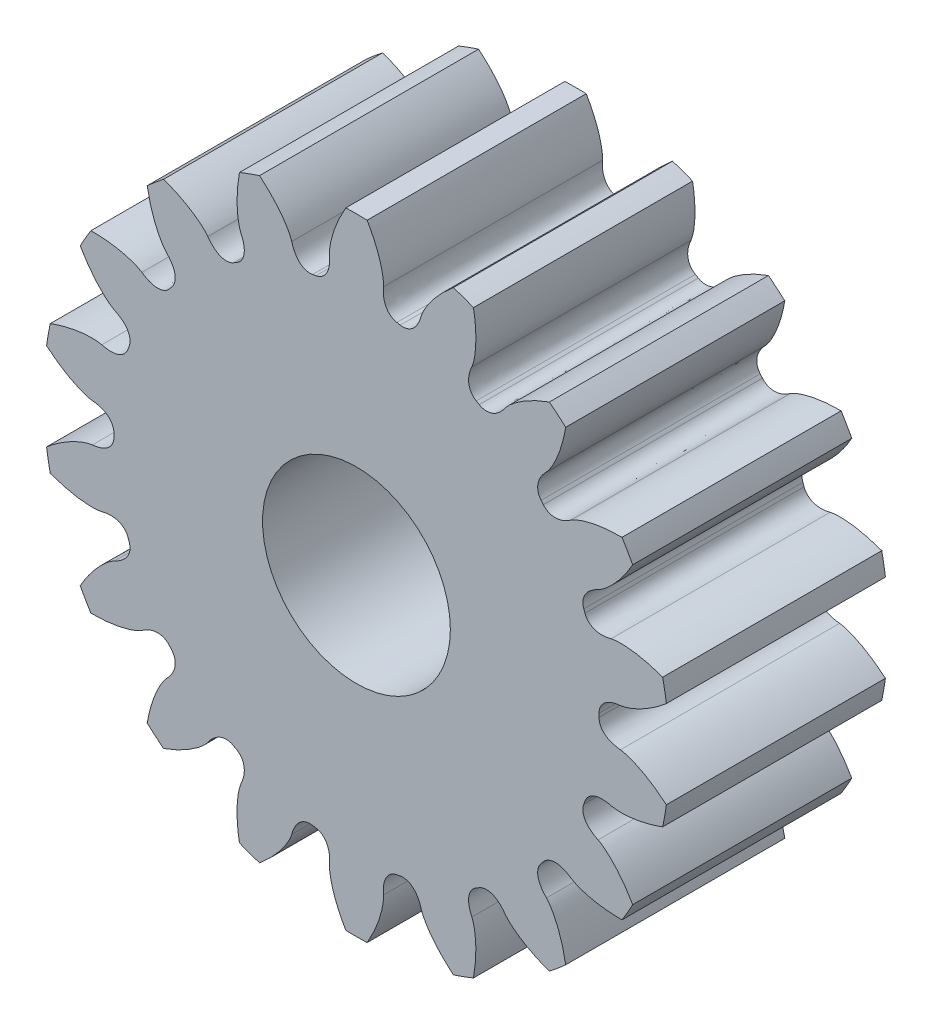
SolidWorks part; units mm, degrees
ref_plane "Спереди" through (0, 0, 0) normal (0, 0, 1) x (1, 0, 0)
ref_plane "Сверху" through (0, 0, 0) normal (0, 1, 0) x (1, 0, 0)
ref_plane "Справа" through (0, 0, 0) normal (1, 0, 0) x (0, 0, -1)
sketch "Model" plane through (0, 0, 0) normal (0, 0, 1) x (1, 0, 0)
  line L0 (-7.7, 0) -> (7.7, 0) construction
  line L1 (0, -7.7) -> (0, 7.7) construction
  arc A0 (0.1704, 4.9971) -> (-0.1704, 4.9971) centre (0, 0) ccw
  arc A1 (-0.6456, 3.8208) -> (-0.7002, 3.8112) centre (0, 0) ccw
  arc A2 (-1.549, 4.754) -> (-1.8692, 4.6375) centre (0, 0) ccw
  arc A3 (-1.9135, 3.3696) -> (-1.9614, 3.3419) centre (0, 0) ccw
  arc A4 (-3.0816, 3.9375) -> (-3.3426, 3.7185) centre (0, 0) ccw
  arc A5 (-2.9505, 2.512) -> (-2.9862, 2.4695) centre (0, 0) ccw
  arc A6 (-4.2424, 2.6461) -> (-4.4128, 2.351) centre (0, 0) ccw
  arc A7 (-3.6317, 1.3513) -> (-3.6507, 1.2993) centre (0, 0) ccw
  arc A8 (-4.8916, 1.0355) -> (-4.9508, 0.6999) centre (0, 0) ccw
  arc A9 (-3.8749, 0.0277) -> (-3.8749, -0.0277) centre (0, 0) ccw
  arc A10 (-4.9508, -0.6999) -> (-4.8916, -1.0355) centre (0, 0) ccw
  arc A11 (-3.6507, -1.2993) -> (-3.6317, -1.3513) centre (0, 0) ccw
  arc A12 (-4.4128, -2.351) -> (-4.2424, -2.6461) centre (0, 0) ccw
  arc A13 (-2.9862, -2.4695) -> (-2.9505, -2.512) centre (0, 0) ccw
  arc A14 (-3.3426, -3.7185) -> (-3.0816, -3.9375) centre (0, 0) ccw
  arc A15 (-1.9614, -3.3419) -> (-1.9135, -3.3696) centre (0, 0) ccw
  arc A16 (-1.8692, -4.6375) -> (-1.549, -4.754) centre (0, 0) ccw
  arc A17 (-0.7002, -3.8112) -> (-0.6456, -3.8208) centre (0, 0) ccw
  arc A18 (-0.1704, -4.9971) -> (0.1704, -4.9971) centre (0, 0) ccw
  arc A19 (0.6456, -3.8208) -> (0.7002, -3.8112) centre (0, 0) ccw
  arc A20 (1.549, -4.754) -> (1.8692, -4.6375) centre (0, 0) ccw
  arc A21 (1.9135, -3.3696) -> (1.9614, -3.3419) centre (0, 0) ccw
  arc A22 (3.0816, -3.9375) -> (3.3426, -3.7185) centre (0, 0) ccw
  arc A23 (2.9505, -2.512) -> (2.9862, -2.4695) centre (0, 0) ccw
  arc A24 (4.2424, -2.6461) -> (4.4128, -2.351) centre (0, 0) ccw
  arc A25 (3.6317, -1.3513) -> (3.6507, -1.2993) centre (0, 0) ccw
  arc A26 (4.8916, -1.0355) -> (4.9508, -0.6999) centre (0, 0) ccw
  arc A27 (3.8749, -0.0277) -> (3.8749, 0.0277) centre (0, 0) ccw
  arc A28 (4.9508, 0.6999) -> (4.8916, 1.0355) centre (0, 0) ccw
  arc A29 (3.6507, 1.2993) -> (3.6317, 1.3513) centre (0, 0) ccw
  arc A30 (4.4128, 2.351) -> (4.2424, 2.6461) centre (0, 0) ccw
  arc A31 (2.9862, 2.4695) -> (2.9505, 2.512) centre (0, 0) ccw
  arc A32 (3.3426, 3.7185) -> (3.0816, 3.9375) centre (0, 0) ccw
  arc A33 (1.9614, 3.3419) -> (1.9135, 3.3696) centre (0, 0) ccw
  arc A34 (1.8692, 4.6375) -> (1.549, 4.754) centre (0, 0) ccw
  arc A35 (0.7002, 3.8112) -> (0.6456, 3.8208) centre (0, 0) ccw
  circle A36 centre (0, 0) radius 4.5 construction
  spline S0 degree 3 poles (0.4314, 4.2073) (0.4264, 4.1628) (0.4271, 4.1189) (0.4335, 4.0758) (0.4372, 4.0511) (0.4421, 4.026) (0.4501, 4.0023) (0.4558, 3.9851) (0.4628, 3.968) (0.4713, 3.952) (0.4783, 3.9388) (0.4864, 3.9259) (0.4954, 3.914) (0.5034, 3.9034) (0.5123, 3.8933) (0.5218, 3.8841) (0.5307, 3.8755) (0.5403, 3.8675) (0.5504, 3.8604) (0.56, 3.8536) (0.5702, 3.8474) (0.5807, 3.8421) (0.5909, 3.837) (0.6017, 3.8326) (0.6125, 3.829) (0.6233, 3.8255) (0.6343, 3.8228) (0.6456, 3.8208) knots 0 0 0 0 1 1 1 2 2 2 3 3 3 4 4 4 5 5 5 6 6 6 7 7 7 8 8 8 9 9 9 9
  spline S1 degree 3 poles (-0.4314, 4.2073) (-0.4264, 4.1628) (-0.4271, 4.1189) (-0.4335, 4.0758) (-0.4372, 4.0511) (-0.4421, 4.026) (-0.4501, 4.0023) (-0.4558, 3.9851) (-0.4628, 3.968) (-0.4713, 3.952) (-0.4783, 3.9388) (-0.4864, 3.9259) (-0.4954, 3.914) (-0.5034, 3.9034) (-0.5123, 3.8933) (-0.5218, 3.8841) (-0.5307, 3.8755) (-0.5403, 3.8675) (-0.5504, 3.8604) (-0.56, 3.8536) (-0.5702, 3.8474) (-0.5807, 3.8421) (-0.5909, 3.837) (-0.6017, 3.8326) (-0.6125, 3.829) (-0.6233, 3.8255) (-0.6343, 3.8228) (-0.6456, 3.8208) knots 0 0 0 0 1 1 1 2 2 2 3 3 3 4 4 4 5 5 5 6 6 6 7 7 7 8 8 8 9 9 9 9
  spline S2 degree 3 poles (0.4314, 4.2073) (0.432, 4.2362) (0.431, 4.265) (0.4284, 4.2936) (0.4258, 4.3229) (0.4209, 4.352) (0.4156, 4.3809) (0.4101, 4.4104) (0.4034, 4.4397) (0.3959, 4.4687) (0.3884, 4.4983) (0.3797, 4.5277) (0.3705, 4.5568) (0.361, 4.5865) (0.3507, 4.6159) (0.3398, 4.6451) (0.3287, 4.6748) (0.3167, 4.7042) (0.3042, 4.7333) (0.2915, 4.763) (0.278, 4.7924) (0.264, 4.8215) (0.2497, 4.8511) (0.2348, 4.8805) (0.2193, 4.9095) (0.2036, 4.939) (0.1873, 4.9682) (0.1704, 4.9971) knots 0 0 0 0 1 1 1 2 2 2 3 3 3 4 4 4 5 5 5 6 6 6 7 7 7 8 8 8 9 9 9 9
  spline S3 degree 3 poles (-0.4314, 4.2073) (-0.432, 4.2362) (-0.431, 4.265) (-0.4284, 4.2936) (-0.4258, 4.3229) (-0.4209, 4.352) (-0.4156, 4.3809) (-0.4101, 4.4104) (-0.4034, 4.4397) (-0.3959, 4.4687) (-0.3884, 4.4983) (-0.3797, 4.5277) (-0.3705, 4.5568) (-0.361, 4.5865) (-0.3507, 4.6159) (-0.3398, 4.6451) (-0.3287, 4.6748) (-0.3167, 4.7042) (-0.3042, 4.7333) (-0.2915, 4.763) (-0.278, 4.7924) (-0.264, 4.8215) (-0.2497, 4.8511) (-0.2348, 4.8805) (-0.2193, 4.9095) (-0.2036, 4.939) (-0.1873, 4.9682) (-0.1704, 4.9971) knots 0 0 0 0 1 1 1 2 2 2 3 3 3 4 4 4 5 5 5 6 6 6 7 7 7 8 8 8 9 9 9 9
  spline S4 degree 3 poles (-1.0336, 4.1011) (-1.0231, 4.0576) (-1.0074, 4.0166) (-0.9866, 3.9783) (-0.9747, 3.9563) (-0.9616, 3.9344) (-0.9459, 3.9148) (-0.9346, 3.9007) (-0.9223, 3.887) (-0.9088, 3.8748) (-0.8977, 3.8649) (-0.8857, 3.8555) (-0.8732, 3.8474) (-0.862, 3.8402) (-0.8502, 3.8337) (-0.8381, 3.8283) (-0.8268, 3.8233) (-0.8151, 3.819) (-0.8032, 3.8158) (-0.7918, 3.8127) (-0.7801, 3.8104) (-0.7684, 3.809) (-0.757, 3.8077) (-0.7454, 3.8072) (-0.734, 3.8076) (-0.7227, 3.808) (-0.7114, 3.8092) (-0.7002, 3.8112) knots 0 0 0 0 1 1 1 2 2 2 3 3 3 4 4 4 5 5 5 6 6 6 7 7 7 8 8 8 9 9 9 9
  spline S5 degree 3 poles (-1.8443, 3.806) (-1.8244, 3.7659) (-1.8101, 3.7245) (-1.8014, 3.6817) (-1.7963, 3.6572) (-1.7924, 3.632) (-1.7918, 3.607) (-1.7913, 3.5888) (-1.792, 3.5704) (-1.7945, 3.5525) (-1.7966, 3.5377) (-1.7998, 3.5228) (-1.8042, 3.5085) (-1.8081, 3.4958) (-1.813, 3.4833) (-1.8188, 3.4714) (-1.8242, 3.4603) (-1.8305, 3.4495) (-1.8375, 3.4393) (-1.8442, 3.4297) (-1.8517, 3.4204) (-1.8598, 3.4118) (-1.8676, 3.4035) (-1.8762, 3.3956) (-1.8852, 3.3886) (-1.8941, 3.3816) (-1.9035, 3.3753) (-1.9135, 3.3696) knots 0 0 0 0 1 1 1 2 2 2 3 3 3 4 4 4 5 5 5 6 6 6 7 7 7 8 8 8 9 9 9 9
  spline S6 degree 3 poles (-1.0336, 4.1011) (-1.043, 4.1285) (-1.0537, 4.1552) (-1.066, 4.1812) (-1.0784, 4.2078) (-1.093, 4.2335) (-1.1079, 4.2588) (-1.123, 4.2847) (-1.1394, 4.3099) (-1.1563, 4.3346) (-1.1736, 4.3599) (-1.1917, 4.3845) (-1.2104, 4.4087) (-1.2294, 4.4334) (-1.2492, 4.4575) (-1.2694, 4.4811) (-1.29, 4.5052) (-1.3113, 4.5288) (-1.333, 4.5519) (-1.3551, 4.5755) (-1.3779, 4.5985) (-1.401, 4.621) (-1.4245, 4.644) (-1.4486, 4.6664) (-1.473, 4.6884) (-1.4979, 4.7108) (-1.5232, 4.7326) (-1.549, 4.754) knots 0 0 0 0 1 1 1 2 2 2 3 3 3 4 4 4 5 5 5 6 6 6 7 7 7 8 8 8 9 9 9 9
  spline S7 degree 3 poles (-1.8443, 3.806) (-1.8548, 3.833) (-1.8637, 3.8604) (-1.8711, 3.8882) (-1.8786, 3.9166) (-1.884, 3.9456) (-1.8889, 3.9746) (-1.8938, 4.0041) (-1.8975, 4.034) (-1.9004, 4.0638) (-1.9034, 4.0942) (-1.9054, 4.1248) (-1.9067, 4.1553) (-1.9079, 4.1864) (-1.9083, 4.2176) (-1.908, 4.2487) (-1.9077, 4.2804) (-1.9065, 4.3122) (-1.9048, 4.3438) (-1.903, 4.3761) (-1.9004, 4.4083) (-1.8971, 4.4404) (-1.8939, 4.4732) (-1.8899, 4.5058) (-1.8853, 4.5384) (-1.8806, 4.5715) (-1.8752, 4.6045) (-1.8692, 4.6375) knots 0 0 0 0 1 1 1 2 2 2 3 3 3 4 4 4 5 5 5 6 6 6 7 7 7 8 8 8 9 9 9 9
  spline S8 degree 3 poles (-2.3739, 3.5002) (-2.3491, 3.463) (-2.3204, 3.4298) (-2.2878, 3.4009) (-2.2691, 3.3843) (-2.2492, 3.3682) (-2.2278, 3.3552) (-2.2124, 3.3458) (-2.1961, 3.3371) (-2.1792, 3.3303) (-2.1654, 3.3248) (-2.151, 3.32) (-2.1364, 3.3167) (-2.1234, 3.3138) (-2.1101, 3.3117) (-2.0969, 3.3108) (-2.0846, 3.3099) (-2.0721, 3.31) (-2.0598, 3.311) (-2.0481, 3.312) (-2.0363, 3.3138) (-2.0248, 3.3165) (-2.0137, 3.3191) (-2.0026, 3.3226) (-1.992, 3.3269) (-1.9815, 3.3311) (-1.9713, 3.3361) (-1.9614, 3.3419) knots 0 0 0 0 1 1 1 2 2 2 3 3 3 4 4 4 5 5 5 6 6 6 7 7 7 8 8 8 9 9 9 9
  spline S9 degree 3 poles (-3.0348, 2.9457) (-3.0024, 2.9148) (-2.9748, 2.8807) (-2.952, 2.8436) (-2.9389, 2.8223) (-2.9265, 2.7999) (-2.9174, 2.7766) (-2.9108, 2.7597) (-2.9051, 2.7422) (-2.9013, 2.7245) (-2.8982, 2.7098) (-2.8961, 2.6948) (-2.8954, 2.6799) (-2.8947, 2.6666) (-2.895, 2.6531) (-2.8964, 2.6399) (-2.8977, 2.6277) (-2.8999, 2.6154) (-2.903, 2.6035) (-2.906, 2.5921) (-2.9098, 2.5808) (-2.9145, 2.57) (-2.919, 2.5595) (-2.9244, 2.5492) (-2.9305, 2.5394) (-2.9364, 2.5298) (-2.9431, 2.5207) (-2.9505, 2.512) knots 0 0 0 0 1 1 1 2 2 2 3 3 3 4 4 4 5 5 5 6 6 6 7 7 7 8 8 8 9 9 9 9
  spline S10 degree 3 poles (-2.3739, 3.5002) (-2.3921, 3.5228) (-2.4113, 3.5442) (-2.4317, 3.5645) (-2.4525, 3.5852) (-2.475, 3.6044) (-2.4977, 3.6231) (-2.5208, 3.6422) (-2.5448, 3.6603) (-2.5691, 3.6777) (-2.594, 3.6955) (-2.6195, 3.7125) (-2.6453, 3.7289) (-2.6716, 3.7455) (-2.6984, 3.7614) (-2.7255, 3.7767) (-2.7531, 3.7923) (-2.7812, 3.8072) (-2.8095, 3.8215) (-2.8383, 3.836) (-2.8675, 3.8499) (-2.897, 3.8632) (-2.9269, 3.8767) (-2.9572, 3.8896) (-2.9877, 3.9019) (-3.0187, 3.9144) (-3.05, 3.9263) (-3.0816, 3.9375) knots 0 0 0 0 1 1 1 2 2 2 3 3 3 4 4 4 5 5 5 6 6 6 7 7 7 8 8 8 9 9 9 9
  spline S11 degree 3 poles (-3.0348, 2.9457) (-3.0539, 2.9675) (-3.0716, 2.9902) (-3.0881, 3.0137) (-3.1049, 3.0378) (-3.1199, 3.0633) (-3.1343, 3.0889) (-3.1491, 3.1149) (-3.1627, 3.1417) (-3.1757, 3.1687) (-3.189, 3.1963) (-3.2012, 3.2243) (-3.2129, 3.2526) (-3.2247, 3.2814) (-3.2357, 3.3106) (-3.2461, 3.3399) (-3.2566, 3.3698) (-3.2664, 3.4) (-3.2756, 3.4304) (-3.2849, 3.4613) (-3.2935, 3.4925) (-3.3015, 3.5238) (-3.3096, 3.5557) (-3.317, 3.5877) (-3.3238, 3.6199) (-3.3307, 3.6526) (-3.337, 3.6855) (-3.3426, 3.7185) knots 0 0 0 0 1 1 1 2 2 2 3 3 3 4 4 4 5 5 5 6 6 6 7 7 7 8 8 8 9 9 9 9
  spline S12 degree 3 poles (-3.4279, 2.4772) (-3.3919, 2.4507) (-3.3535, 2.4294) (-3.313, 2.4133) (-3.2897, 2.4041) (-3.2656, 2.3958) (-3.241, 2.3909) (-3.2233, 2.3873) (-3.205, 2.3848) (-3.1869, 2.3842) (-3.1719, 2.3837) (-3.1568, 2.3841) (-3.1419, 2.386) (-3.1288, 2.3877) (-3.1155, 2.3903) (-3.1028, 2.3939) (-3.0909, 2.3974) (-3.0792, 2.4017) (-3.068, 2.4068) (-3.0573, 2.4117) (-3.0469, 2.4175) (-3.037, 2.424) (-3.0275, 2.4303) (-3.0183, 2.4373) (-3.0097, 2.445) (-3.0013, 2.4525) (-2.9935, 2.4607) (-2.9862, 2.4695) knots 0 0 0 0 1 1 1 2 2 2 3 3 3 4 4 4 5 5 5 6 6 6 7 7 7 8 8 8 9 9 9 9
  spline S13 degree 3 poles (-3.8593, 1.7301) (-3.8183, 1.7121) (-3.7807, 1.6896) (-3.7465, 1.6625) (-3.7269, 1.6469) (-3.7076, 1.6301) (-3.6911, 1.6114) (-3.6791, 1.5978) (-3.6678, 1.5832) (-3.6582, 1.5678) (-3.6503, 1.5551) (-3.6431, 1.5418) (-3.6373, 1.528) (-3.6322, 1.5157) (-3.6278, 1.503) (-3.6246, 1.4901) (-3.6216, 1.4782) (-3.6195, 1.4658) (-3.6184, 1.4536) (-3.6173, 1.4419) (-3.617, 1.4299) (-3.6177, 1.4182) (-3.6184, 1.4067) (-3.6199, 1.3952) (-3.6223, 1.384) (-3.6246, 1.373) (-3.6278, 1.3621) (-3.6317, 1.3513) knots 0 0 0 0 1 1 1 2 2 2 3 3 3 4 4 4 5 5 5 6 6 6 7 7 7 8 8 8 9 9 9 9
  spline S14 degree 3 poles (-3.4279, 2.4772) (-3.4527, 2.4922) (-3.4781, 2.5057) (-3.5042, 2.5178) (-3.5308, 2.5302) (-3.5585, 2.5405) (-3.5862, 2.5504) (-3.6144, 2.5604) (-3.6432, 2.5691) (-3.6721, 2.5772) (-3.7015, 2.5855) (-3.7312, 2.5927) (-3.7611, 2.5992) (-3.7915, 2.6059) (-3.8221, 2.6117) (-3.8529, 2.6168) (-3.8841, 2.622) (-3.9156, 2.6264) (-3.9471, 2.6301) (-3.9792, 2.6339) (-4.0113, 2.637) (-4.0436, 2.6394) (-4.0763, 2.6419) (-4.1092, 2.6436) (-4.1421, 2.6447) (-4.1755, 2.6458) (-4.2089, 2.6463) (-4.2424, 2.6461) knots 0 0 0 0 1 1 1 2 2 2 3 3 3 4 4 4 5 5 5 6 6 6 7 7 7 8 8 8 9 9 9 9
  spline S15 degree 3 poles (-3.8593, 1.7301) (-3.8846, 1.744) (-3.9091, 1.7593) (-3.9326, 1.7758) (-3.9566, 1.7927) (-3.9794, 1.8115) (-4.0018, 1.8306) (-4.0246, 1.85) (-4.0465, 1.8705) (-4.068, 1.8915) (-4.0898, 1.9128) (-4.111, 1.935) (-4.1316, 1.9576) (-4.1525, 1.9806) (-4.1729, 2.0042) (-4.1926, 2.0283) (-4.2128, 2.0528) (-4.2323, 2.0778) (-4.2513, 2.1032) (-4.2706, 2.1291) (-4.2894, 2.1554) (-4.3076, 2.1821) (-4.3261, 2.2093) (-4.344, 2.2369) (-4.3614, 2.2648) (-4.3791, 2.2932) (-4.3962, 2.3219) (-4.4128, 2.351) knots 0 0 0 0 1 1 1 2 2 2 3 3 3 4 4 4 5 5 5 6 6 6 7 7 7 8 8 8 9 9 9 9
  spline S16 degree 3 poles (-4.0684, 1.1554) (-4.0255, 1.1428) (-3.9822, 1.1359) (-3.9386, 1.1347) (-3.9136, 1.134) (-3.888, 1.1345) (-3.8633, 1.1382) (-3.8454, 1.1409) (-3.8273, 1.1448) (-3.8101, 1.1504) (-3.7959, 1.155) (-3.7818, 1.1607) (-3.7685, 1.1675) (-3.7567, 1.1736) (-3.7452, 1.1806) (-3.7344, 1.1884) (-3.7245, 1.1956) (-3.7149, 1.2037) (-3.7062, 1.2123) (-3.6978, 1.2206) (-3.69, 1.2296) (-3.6829, 1.239) (-3.6761, 1.2482) (-3.6699, 1.258) (-3.6645, 1.2681) (-3.6591, 1.2781) (-3.6545, 1.2885) (-3.6507, 1.2993) knots 0 0 0 0 1 1 1 2 2 2 3 3 3 4 4 4 5 5 5 6 6 6 7 7 7 8 8 8 9 9 9 9
  spline S17 degree 3 poles (-4.2183, 0.3058) (-4.1736, 0.3029) (-4.1305, 0.2946) (-4.0892, 0.2808) (-4.0654, 0.2729) (-4.0416, 0.2637) (-4.0196, 0.2518) (-4.0037, 0.2431) (-3.9881, 0.2333) (-3.9738, 0.2221) (-3.962, 0.2129) (-3.9507, 0.2028) (-3.9406, 0.1918) (-3.9315, 0.1821) (-3.9231, 0.1716) (-3.9157, 0.1606) (-3.9088, 0.1503) (-3.9026, 0.1395) (-3.8973, 0.1284) (-3.8923, 0.1177) (-3.888, 0.1066) (-3.8846, 0.0953) (-3.8813, 0.0843) (-3.8788, 0.073) (-3.8772, 0.0617) (-3.8756, 0.0505) (-3.8748, 0.0391) (-3.8749, 0.0277) knots 0 0 0 0 1 1 1 2 2 2 3 3 3 4 4 4 5 5 5 6 6 6 7 7 7 8 8 8 9 9 9 9
  spline S18 degree 3 poles (-4.0684, 1.1554) (-4.0968, 1.161) (-4.1254, 1.165) (-4.154, 1.1675) (-4.1833, 1.17) (-4.2128, 1.1702) (-4.2422, 1.17) (-4.2722, 1.1698) (-4.3022, 1.1682) (-4.3321, 1.1659) (-4.3625, 1.1636) (-4.393, 1.1602) (-4.4232, 1.1561) (-4.4541, 1.152) (-4.4849, 1.1469) (-4.5155, 1.1412) (-4.5467, 1.1354) (-4.5777, 1.1288) (-4.6086, 1.1215) (-4.64, 1.1141) (-4.6713, 1.106) (-4.7024, 1.0972) (-4.7341, 1.0883) (-4.7655, 1.0787) (-4.7968, 1.0685) (-4.8286, 1.0582) (-4.8602, 1.0472) (-4.8916, 1.0355) knots 0 0 0 0 1 1 1 2 2 2 3 3 3 4 4 4 5 5 5 6 6 6 7 7 7 8 8 8 9 9 9 9
  spline S19 degree 3 poles (-4.2183, 0.3058) (-4.2468, 0.3102) (-4.275, 0.3162) (-4.3028, 0.3237) (-4.3311, 0.3314) (-4.359, 0.3412) (-4.3865, 0.3515) (-4.4146, 0.362) (-4.4423, 0.3737) (-4.4696, 0.3861) (-4.4974, 0.3987) (-4.5248, 0.4123) (-4.5519, 0.4264) (-4.5795, 0.4409) (-4.6067, 0.4562) (-4.6335, 0.472) (-4.6608, 0.4881) (-4.6877, 0.505) (-4.7143, 0.5223) (-4.7413, 0.54) (-4.7679, 0.5584) (-4.7941, 0.5773) (-4.8208, 0.5964) (-4.8471, 0.6162) (-4.873, 0.6365) (-4.8993, 0.6571) (-4.9252, 0.6783) (-4.9508, 0.6999) knots 0 0 0 0 1 1 1 2 2 2 3 3 3 4 4 4 5 5 5 6 6 6 7 7 7 8 8 8 9 9 9 9
  spline S20 degree 3 poles (-4.2183, -0.3058) (-4.1736, -0.3029) (-4.1305, -0.2946) (-4.0892, -0.2808) (-4.0654, -0.2729) (-4.0416, -0.2637) (-4.0196, -0.2518) (-4.0037, -0.2431) (-3.9881, -0.2333) (-3.9738, -0.2221) (-3.962, -0.2129) (-3.9507, -0.2028) (-3.9406, -0.1918) (-3.9315, -0.1821) (-3.9231, -0.1716) (-3.9157, -0.1606) (-3.9088, -0.1503) (-3.9026, -0.1395) (-3.8973, -0.1284) (-3.8923, -0.1177) (-3.888, -0.1066) (-3.8846, -0.0953) (-3.8813, -0.0843) (-3.8788, -0.073) (-3.8772, -0.0617) (-3.8756, -0.0505) (-3.8748, -0.0391) (-3.8749, -0.0277) knots 0 0 0 0 1 1 1 2 2 2 3 3 3 4 4 4 5 5 5 6 6 6 7 7 7 8 8 8 9 9 9 9
  spline S21 degree 3 poles (-4.0684, -1.1554) (-4.0255, -1.1428) (-3.9822, -1.1359) (-3.9386, -1.1347) (-3.9136, -1.134) (-3.888, -1.1345) (-3.8633, -1.1382) (-3.8454, -1.1409) (-3.8273, -1.1448) (-3.8101, -1.1504) (-3.7959, -1.155) (-3.7818, -1.1607) (-3.7685, -1.1675) (-3.7567, -1.1736) (-3.7452, -1.1806) (-3.7344, -1.1884) (-3.7245, -1.1956) (-3.7149, -1.2037) (-3.7062, -1.2123) (-3.6978, -1.2206) (-3.69, -1.2296) (-3.6829, -1.239) (-3.6761, -1.2482) (-3.6699, -1.258) (-3.6645, -1.2681) (-3.6591, -1.2781) (-3.6545, -1.2885) (-3.6507, -1.2993) knots 0 0 0 0 1 1 1 2 2 2 3 3 3 4 4 4 5 5 5 6 6 6 7 7 7 8 8 8 9 9 9 9
  spline S22 degree 3 poles (-4.2183, -0.3058) (-4.2468, -0.3102) (-4.275, -0.3162) (-4.3028, -0.3237) (-4.3311, -0.3314) (-4.359, -0.3412) (-4.3865, -0.3515) (-4.4146, -0.362) (-4.4423, -0.3737) (-4.4696, -0.3861) (-4.4974, -0.3987) (-4.5248, -0.4123) (-4.5519, -0.4264) (-4.5795, -0.4409) (-4.6067, -0.4562) (-4.6335, -0.472) (-4.6608, -0.4881) (-4.6877, -0.505) (-4.7143, -0.5223) (-4.7413, -0.54) (-4.7679, -0.5584) (-4.7941, -0.5773) (-4.8208, -0.5964) (-4.8471, -0.6162) (-4.873, -0.6365) (-4.8993, -0.6571) (-4.9252, -0.6783) (-4.9508, -0.6999) knots 0 0 0 0 1 1 1 2 2 2 3 3 3 4 4 4 5 5 5 6 6 6 7 7 7 8 8 8 9 9 9 9
  spline S23 degree 3 poles (-4.0684, -1.1554) (-4.0968, -1.161) (-4.1254, -1.165) (-4.154, -1.1675) (-4.1833, -1.17) (-4.2128, -1.1702) (-4.2422, -1.17) (-4.2722, -1.1698) (-4.3022, -1.1682) (-4.3321, -1.1659) (-4.3625, -1.1636) (-4.393, -1.1602) (-4.4232, -1.1561) (-4.4541, -1.152) (-4.4849, -1.1469) (-4.5155, -1.1412) (-4.5467, -1.1354) (-4.5777, -1.1288) (-4.6086, -1.1215) (-4.64, -1.1141) (-4.6713, -1.106) (-4.7024, -1.0972) (-4.7341, -1.0883) (-4.7655, -1.0787) (-4.7968, -1.0685) (-4.8286, -1.0582) (-4.8602, -1.0472) (-4.8916, -1.0355) knots 0 0 0 0 1 1 1 2 2 2 3 3 3 4 4 4 5 5 5 6 6 6 7 7 7 8 8 8 9 9 9 9
  spline S24 degree 3 poles (-3.8593, -1.7301) (-3.8183, -1.7121) (-3.7807, -1.6896) (-3.7465, -1.6625) (-3.7269, -1.6469) (-3.7076, -1.6301) (-3.6911, -1.6114) (-3.6791, -1.5978) (-3.6678, -1.5832) (-3.6582, -1.5678) (-3.6503, -1.5551) (-3.6431, -1.5418) (-3.6373, -1.528) (-3.6322, -1.5157) (-3.6278, -1.503) (-3.6246, -1.4901) (-3.6216, -1.4782) (-3.6195, -1.4658) (-3.6184, -1.4536) (-3.6173, -1.4419) (-3.617, -1.4299) (-3.6177, -1.4182) (-3.6184, -1.4067) (-3.6199, -1.3952) (-3.6223, -1.384) (-3.6246, -1.373) (-3.6278, -1.3621) (-3.6317, -1.3513) knots 0 0 0 0 1 1 1 2 2 2 3 3 3 4 4 4 5 5 5 6 6 6 7 7 7 8 8 8 9 9 9 9
  spline S25 degree 3 poles (-3.4279, -2.4772) (-3.3919, -2.4507) (-3.3535, -2.4294) (-3.313, -2.4133) (-3.2897, -2.4041) (-3.2656, -2.3958) (-3.241, -2.3909) (-3.2233, -2.3873) (-3.205, -2.3848) (-3.1869, -2.3842) (-3.1719, -2.3837) (-3.1568, -2.3841) (-3.1419, -2.386) (-3.1288, -2.3877) (-3.1155, -2.3903) (-3.1028, -2.3939) (-3.0909, -2.3974) (-3.0792, -2.4017) (-3.068, -2.4068) (-3.0573, -2.4117) (-3.0469, -2.4175) (-3.037, -2.424) (-3.0275, -2.4303) (-3.0183, -2.4373) (-3.0097, -2.445) (-3.0013, -2.4525) (-2.9935, -2.4607) (-2.9862, -2.4695) knots 0 0 0 0 1 1 1 2 2 2 3 3 3 4 4 4 5 5 5 6 6 6 7 7 7 8 8 8 9 9 9 9
  spline S26 degree 3 poles (-3.8593, -1.7301) (-3.8846, -1.744) (-3.9091, -1.7593) (-3.9326, -1.7758) (-3.9566, -1.7927) (-3.9794, -1.8115) (-4.0018, -1.8306) (-4.0246, -1.85) (-4.0465, -1.8705) (-4.068, -1.8915) (-4.0898, -1.9128) (-4.111, -1.935) (-4.1316, -1.9576) (-4.1525, -1.9806) (-4.1729, -2.0042) (-4.1926, -2.0283) (-4.2128, -2.0528) (-4.2323, -2.0778) (-4.2513, -2.1032) (-4.2706, -2.1291) (-4.2894, -2.1554) (-4.3076, -2.1821) (-4.3261, -2.2093) (-4.344, -2.2369) (-4.3614, -2.2648) (-4.3791, -2.2932) (-4.3962, -2.3219) (-4.4128, -2.351) knots 0 0 0 0 1 1 1 2 2 2 3 3 3 4 4 4 5 5 5 6 6 6 7 7 7 8 8 8 9 9 9 9
  spline S27 degree 3 poles (-3.4279, -2.4772) (-3.4527, -2.4922) (-3.4781, -2.5057) (-3.5042, -2.5178) (-3.5308, -2.5302) (-3.5585, -2.5405) (-3.5862, -2.5504) (-3.6144, -2.5604) (-3.6432, -2.5691) (-3.6721, -2.5772) (-3.7015, -2.5855) (-3.7312, -2.5927) (-3.7611, -2.5992) (-3.7915, -2.6059) (-3.8221, -2.6117) (-3.8529, -2.6168) (-3.8841, -2.622) (-3.9156, -2.6264) (-3.9471, -2.6301) (-3.9792, -2.6339) (-4.0113, -2.637) (-4.0436, -2.6394) (-4.0763, -2.6419) (-4.1092, -2.6436) (-4.1421, -2.6447) (-4.1755, -2.6458) (-4.2089, -2.6463) (-4.2424, -2.6461) knots 0 0 0 0 1 1 1 2 2 2 3 3 3 4 4 4 5 5 5 6 6 6 7 7 7 8 8 8 9 9 9 9
  spline S28 degree 3 poles (-3.0348, -2.9457) (-3.0024, -2.9148) (-2.9748, -2.8807) (-2.952, -2.8436) (-2.9389, -2.8223) (-2.9265, -2.7999) (-2.9174, -2.7766) (-2.9108, -2.7597) (-2.9051, -2.7422) (-2.9013, -2.7245) (-2.8982, -2.7098) (-2.8961, -2.6948) (-2.8954, -2.6799) (-2.8947, -2.6666) (-2.895, -2.6531) (-2.8964, -2.6399) (-2.8977, -2.6277) (-2.8999, -2.6154) (-2.903, -2.6035) (-2.906, -2.5921) (-2.9098, -2.5808) (-2.9145, -2.57) (-2.919, -2.5595) (-2.9244, -2.5492) (-2.9305, -2.5394) (-2.9364, -2.5298) (-2.9431, -2.5207) (-2.9505, -2.512) knots 0 0 0 0 1 1 1 2 2 2 3 3 3 4 4 4 5 5 5 6 6 6 7 7 7 8 8 8 9 9 9 9
  spline S29 degree 3 poles (-2.3739, -3.5002) (-2.3491, -3.463) (-2.3204, -3.4298) (-2.2878, -3.4009) (-2.2691, -3.3843) (-2.2492, -3.3682) (-2.2278, -3.3552) (-2.2124, -3.3458) (-2.1961, -3.3371) (-2.1792, -3.3303) (-2.1654, -3.3248) (-2.151, -3.32) (-2.1364, -3.3167) (-2.1234, -3.3138) (-2.1101, -3.3117) (-2.0969, -3.3108) (-2.0846, -3.3099) (-2.0721, -3.31) (-2.0598, -3.311) (-2.0481, -3.312) (-2.0363, -3.3138) (-2.0248, -3.3165) (-2.0137, -3.3191) (-2.0026, -3.3226) (-1.992, -3.3269) (-1.9815, -3.3311) (-1.9713, -3.3361) (-1.9614, -3.3419) knots 0 0 0 0 1 1 1 2 2 2 3 3 3 4 4 4 5 5 5 6 6 6 7 7 7 8 8 8 9 9 9 9
  spline S30 degree 3 poles (-3.0348, -2.9457) (-3.0539, -2.9675) (-3.0716, -2.9902) (-3.0881, -3.0137) (-3.1049, -3.0378) (-3.1199, -3.0633) (-3.1343, -3.0889) (-3.1491, -3.1149) (-3.1627, -3.1417) (-3.1757, -3.1687) (-3.189, -3.1963) (-3.2012, -3.2243) (-3.2129, -3.2526) (-3.2247, -3.2814) (-3.2357, -3.3106) (-3.2461, -3.3399) (-3.2566, -3.3698) (-3.2664, -3.4) (-3.2756, -3.4304) (-3.2849, -3.4613) (-3.2935, -3.4925) (-3.3015, -3.5238) (-3.3096, -3.5557) (-3.317, -3.5877) (-3.3238, -3.6199) (-3.3307, -3.6526) (-3.337, -3.6855) (-3.3426, -3.7185) knots 0 0 0 0 1 1 1 2 2 2 3 3 3 4 4 4 5 5 5 6 6 6 7 7 7 8 8 8 9 9 9 9
  spline S31 degree 3 poles (-2.3739, -3.5002) (-2.3921, -3.5228) (-2.4113, -3.5442) (-2.4317, -3.5645) (-2.4525, -3.5852) (-2.475, -3.6044) (-2.4977, -3.6231) (-2.5208, -3.6422) (-2.5448, -3.6603) (-2.5691, -3.6777) (-2.594, -3.6955) (-2.6195, -3.7125) (-2.6453, -3.7289) (-2.6716, -3.7455) (-2.6984, -3.7614) (-2.7255, -3.7767) (-2.7531, -3.7923) (-2.7812, -3.8072) (-2.8095, -3.8215) (-2.8383, -3.836) (-2.8675, -3.8499) (-2.897, -3.8632) (-2.9269, -3.8767) (-2.9572, -3.8896) (-2.9877, -3.9019) (-3.0187, -3.9144) (-3.05, -3.9263) (-3.0816, -3.9375) knots 0 0 0 0 1 1 1 2 2 2 3 3 3 4 4 4 5 5 5 6 6 6 7 7 7 8 8 8 9 9 9 9
  spline S32 degree 3 poles (-1.8443, -3.806) (-1.8244, -3.7659) (-1.8101, -3.7245) (-1.8014, -3.6817) (-1.7963, -3.6572) (-1.7924, -3.632) (-1.7918, -3.607) (-1.7913, -3.5888) (-1.792, -3.5704) (-1.7945, -3.5525) (-1.7966, -3.5377) (-1.7998, -3.5228) (-1.8042, -3.5085) (-1.8081, -3.4958) (-1.813, -3.4833) (-1.8188, -3.4714) (-1.8242, -3.4603) (-1.8305, -3.4495) (-1.8375, -3.4393) (-1.8442, -3.4297) (-1.8517, -3.4204) (-1.8598, -3.4118) (-1.8676, -3.4035) (-1.8762, -3.3956) (-1.8852, -3.3886) (-1.8941, -3.3816) (-1.9035, -3.3753) (-1.9135, -3.3696) knots 0 0 0 0 1 1 1 2 2 2 3 3 3 4 4 4 5 5 5 6 6 6 7 7 7 8 8 8 9 9 9 9
  spline S33 degree 3 poles (-1.0336, -4.1011) (-1.0231, -4.0576) (-1.0074, -4.0166) (-0.9866, -3.9783) (-0.9747, -3.9563) (-0.9616, -3.9344) (-0.9459, -3.9148) (-0.9346, -3.9007) (-0.9223, -3.887) (-0.9088, -3.8748) (-0.8977, -3.8649) (-0.8857, -3.8555) (-0.8732, -3.8474) (-0.862, -3.8402) (-0.8502, -3.8337) (-0.8381, -3.8283) (-0.8268, -3.8233) (-0.8151, -3.819) (-0.8032, -3.8158) (-0.7918, -3.8127) (-0.7801, -3.8104) (-0.7684, -3.809) (-0.757, -3.8077) (-0.7454, -3.8072) (-0.734, -3.8076) (-0.7227, -3.808) (-0.7114, -3.8092) (-0.7002, -3.8112) knots 0 0 0 0 1 1 1 2 2 2 3 3 3 4 4 4 5 5 5 6 6 6 7 7 7 8 8 8 9 9 9 9
  spline S34 degree 3 poles (-1.8443, -3.806) (-1.8548, -3.833) (-1.8637, -3.8604) (-1.8711, -3.8882) (-1.8786, -3.9166) (-1.884, -3.9456) (-1.8889, -3.9746) (-1.8938, -4.0041) (-1.8975, -4.034) (-1.9004, -4.0638) (-1.9034, -4.0942) (-1.9054, -4.1248) (-1.9067, -4.1553) (-1.9079, -4.1864) (-1.9083, -4.2176) (-1.908, -4.2487) (-1.9077, -4.2804) (-1.9065, -4.3122) (-1.9048, -4.3438) (-1.903, -4.3761) (-1.9004, -4.4083) (-1.8971, -4.4404) (-1.8939, -4.4732) (-1.8899, -4.5058) (-1.8853, -4.5384) (-1.8806, -4.5715) (-1.8752, -4.6045) (-1.8692, -4.6375) knots 0 0 0 0 1 1 1 2 2 2 3 3 3 4 4 4 5 5 5 6 6 6 7 7 7 8 8 8 9 9 9 9
  spline S35 degree 3 poles (-1.0336, -4.1011) (-1.043, -4.1285) (-1.0537, -4.1552) (-1.066, -4.1812) (-1.0784, -4.2078) (-1.093, -4.2335) (-1.1079, -4.2588) (-1.123, -4.2847) (-1.1394, -4.3099) (-1.1563, -4.3346) (-1.1736, -4.3599) (-1.1917, -4.3845) (-1.2104, -4.4087) (-1.2294, -4.4334) (-1.2492, -4.4575) (-1.2694, -4.4811) (-1.29, -4.5052) (-1.3113, -4.5288) (-1.333, -4.5519) (-1.3551, -4.5755) (-1.3779, -4.5985) (-1.401, -4.621) (-1.4245, -4.644) (-1.4486, -4.6664) (-1.473, -4.6884) (-1.4979, -4.7108) (-1.5232, -4.7326) (-1.549, -4.754) knots 0 0 0 0 1 1 1 2 2 2 3 3 3 4 4 4 5 5 5 6 6 6 7 7 7 8 8 8 9 9 9 9
  spline S36 degree 3 poles (-0.4314, -4.2073) (-0.4264, -4.1628) (-0.4271, -4.1189) (-0.4335, -4.0758) (-0.4372, -4.0511) (-0.4421, -4.026) (-0.4501, -4.0023) (-0.4558, -3.9851) (-0.4628, -3.968) (-0.4713, -3.952) (-0.4783, -3.9388) (-0.4864, -3.9259) (-0.4954, -3.914) (-0.5034, -3.9034) (-0.5123, -3.8933) (-0.5218, -3.8841) (-0.5307, -3.8755) (-0.5403, -3.8675) (-0.5504, -3.8604) (-0.56, -3.8536) (-0.5702, -3.8474) (-0.5807, -3.8421) (-0.5909, -3.837) (-0.6017, -3.8326) (-0.6125, -3.829) (-0.6233, -3.8255) (-0.6343, -3.8228) (-0.6456, -3.8208) knots 0 0 0 0 1 1 1 2 2 2 3 3 3 4 4 4 5 5 5 6 6 6 7 7 7 8 8 8 9 9 9 9
  spline S37 degree 3 poles (0.4314, -4.2073) (0.4264, -4.1628) (0.4271, -4.1189) (0.4335, -4.0758) (0.4372, -4.0511) (0.4421, -4.026) (0.4501, -4.0023) (0.4558, -3.9851) (0.4628, -3.968) (0.4713, -3.952) (0.4783, -3.9388) (0.4864, -3.9259) (0.4954, -3.914) (0.5034, -3.9034) (0.5123, -3.8933) (0.5218, -3.8841) (0.5307, -3.8755) (0.5403, -3.8675) (0.5504, -3.8604) (0.56, -3.8536) (0.5702, -3.8474) (0.5807, -3.8421) (0.5909, -3.837) (0.6017, -3.8326) (0.6125, -3.829) (0.6233, -3.8255) (0.6343, -3.8228) (0.6456, -3.8208) knots 0 0 0 0 1 1 1 2 2 2 3 3 3 4 4 4 5 5 5 6 6 6 7 7 7 8 8 8 9 9 9 9
  spline S38 degree 3 poles (-0.4314, -4.2073) (-0.432, -4.2362) (-0.431, -4.265) (-0.4284, -4.2936) (-0.4258, -4.3229) (-0.4209, -4.352) (-0.4156, -4.3809) (-0.4101, -4.4104) (-0.4034, -4.4397) (-0.3959, -4.4687) (-0.3884, -4.4983) (-0.3797, -4.5277) (-0.3705, -4.5568) (-0.361, -4.5865) (-0.3507, -4.6159) (-0.3398, -4.6451) (-0.3287, -4.6748) (-0.3167, -4.7042) (-0.3042, -4.7333) (-0.2915, -4.763) (-0.278, -4.7924) (-0.264, -4.8215) (-0.2497, -4.8511) (-0.2348, -4.8805) (-0.2193, -4.9095) (-0.2036, -4.939) (-0.1873, -4.9682) (-0.1704, -4.9971) knots 0 0 0 0 1 1 1 2 2 2 3 3 3 4 4 4 5 5 5 6 6 6 7 7 7 8 8 8 9 9 9 9
  spline S39 degree 3 poles (0.4314, -4.2073) (0.432, -4.2362) (0.431, -4.265) (0.4284, -4.2936) (0.4258, -4.3229) (0.4209, -4.352) (0.4156, -4.3809) (0.4101, -4.4104) (0.4034, -4.4397) (0.3959, -4.4687) (0.3884, -4.4983) (0.3797, -4.5277) (0.3705, -4.5568) (0.361, -4.5865) (0.3507, -4.6159) (0.3398, -4.6451) (0.3287, -4.6748) (0.3167, -4.7042) (0.3042, -4.7333) (0.2915, -4.763) (0.278, -4.7924) (0.264, -4.8215) (0.2497, -4.8511) (0.2348, -4.8805) (0.2193, -4.9095) (0.2036, -4.939) (0.1873, -4.9682) (0.1704, -4.9971) knots 0 0 0 0 1 1 1 2 2 2 3 3 3 4 4 4 5 5 5 6 6 6 7 7 7 8 8 8 9 9 9 9
  spline S40 degree 3 poles (1.0336, -4.1011) (1.0231, -4.0576) (1.0074, -4.0166) (0.9866, -3.9783) (0.9747, -3.9563) (0.9616, -3.9344) (0.9459, -3.9148) (0.9346, -3.9007) (0.9223, -3.887) (0.9088, -3.8748) (0.8977, -3.8649) (0.8857, -3.8555) (0.8732, -3.8474) (0.862, -3.8402) (0.8502, -3.8337) (0.8381, -3.8283) (0.8268, -3.8233) (0.8151, -3.819) (0.8032, -3.8158) (0.7918, -3.8127) (0.7801, -3.8104) (0.7684, -3.809) (0.757, -3.8077) (0.7454, -3.8072) (0.734, -3.8076) (0.7227, -3.808) (0.7114, -3.8092) (0.7002, -3.8112) knots 0 0 0 0 1 1 1 2 2 2 3 3 3 4 4 4 5 5 5 6 6 6 7 7 7 8 8 8 9 9 9 9
  spline S41 degree 3 poles (1.8443, -3.806) (1.8244, -3.7659) (1.8101, -3.7245) (1.8014, -3.6817) (1.7963, -3.6572) (1.7924, -3.632) (1.7918, -3.607) (1.7913, -3.5888) (1.792, -3.5704) (1.7945, -3.5525) (1.7966, -3.5377) (1.7998, -3.5228) (1.8042, -3.5085) (1.8081, -3.4958) (1.813, -3.4833) (1.8188, -3.4714) (1.8242, -3.4603) (1.8305, -3.4495) (1.8375, -3.4393) (1.8442, -3.4297) (1.8517, -3.4204) (1.8598, -3.4118) (1.8676, -3.4035) (1.8762, -3.3956) (1.8852, -3.3886) (1.8941, -3.3816) (1.9035, -3.3753) (1.9135, -3.3696) knots 0 0 0 0 1 1 1 2 2 2 3 3 3 4 4 4 5 5 5 6 6 6 7 7 7 8 8 8 9 9 9 9
  spline S42 degree 3 poles (1.0336, -4.1011) (1.043, -4.1285) (1.0537, -4.1552) (1.066, -4.1812) (1.0784, -4.2078) (1.093, -4.2335) (1.1079, -4.2588) (1.123, -4.2847) (1.1394, -4.3099) (1.1563, -4.3346) (1.1736, -4.3599) (1.1917, -4.3845) (1.2104, -4.4087) (1.2294, -4.4334) (1.2492, -4.4575) (1.2694, -4.4811) (1.29, -4.5052) (1.3113, -4.5288) (1.333, -4.5519) (1.3551, -4.5755) (1.3779, -4.5985) (1.401, -4.621) (1.4245, -4.644) (1.4486, -4.6664) (1.473, -4.6884) (1.4979, -4.7108) (1.5232, -4.7326) (1.549, -4.754) knots 0 0 0 0 1 1 1 2 2 2 3 3 3 4 4 4 5 5 5 6 6 6 7 7 7 8 8 8 9 9 9 9
  spline S43 degree 3 poles (1.8443, -3.806) (1.8548, -3.833) (1.8637, -3.8604) (1.8711, -3.8882) (1.8786, -3.9166) (1.884, -3.9456) (1.8889, -3.9746) (1.8938, -4.0041) (1.8975, -4.034) (1.9004, -4.0638) (1.9034, -4.0942) (1.9054, -4.1248) (1.9067, -4.1553) (1.9079, -4.1864) (1.9083, -4.2176) (1.908, -4.2487) (1.9077, -4.2804) (1.9065, -4.3122) (1.9048, -4.3438) (1.903, -4.3761) (1.9004, -4.4083) (1.8971, -4.4404) (1.8939, -4.4732) (1.8899, -4.5058) (1.8853, -4.5384) (1.8806, -4.5715) (1.8752, -4.6045) (1.8692, -4.6375) knots 0 0 0 0 1 1 1 2 2 2 3 3 3 4 4 4 5 5 5 6 6 6 7 7 7 8 8 8 9 9 9 9
  spline S44 degree 3 poles (2.3739, -3.5002) (2.3491, -3.463) (2.3204, -3.4298) (2.2878, -3.4009) (2.2691, -3.3843) (2.2492, -3.3682) (2.2278, -3.3552) (2.2124, -3.3458) (2.1961, -3.3371) (2.1792, -3.3303) (2.1654, -3.3248) (2.151, -3.32) (2.1364, -3.3167) (2.1234, -3.3138) (2.1101, -3.3117) (2.0969, -3.3108) (2.0846, -3.3099) (2.0721, -3.31) (2.0598, -3.311) (2.0481, -3.312) (2.0363, -3.3138) (2.0248, -3.3165) (2.0137, -3.3191) (2.0026, -3.3226) (1.992, -3.3269) (1.9815, -3.3311) (1.9713, -3.3361) (1.9614, -3.3419) knots 0 0 0 0 1 1 1 2 2 2 3 3 3 4 4 4 5 5 5 6 6 6 7 7 7 8 8 8 9 9 9 9
  spline S45 degree 3 poles (3.0348, -2.9457) (3.0024, -2.9148) (2.9748, -2.8807) (2.952, -2.8436) (2.9389, -2.8223) (2.9265, -2.7999) (2.9174, -2.7766) (2.9108, -2.7597) (2.9051, -2.7422) (2.9013, -2.7245) (2.8982, -2.7098) (2.8961, -2.6948) (2.8954, -2.6799) (2.8947, -2.6666) (2.895, -2.6531) (2.8964, -2.6399) (2.8977, -2.6277) (2.8999, -2.6154) (2.903, -2.6035) (2.906, -2.5921) (2.9098, -2.5808) (2.9145, -2.57) (2.919, -2.5595) (2.9244, -2.5492) (2.9305, -2.5394) (2.9364, -2.5298) (2.9431, -2.5207) (2.9505, -2.512) knots 0 0 0 0 1 1 1 2 2 2 3 3 3 4 4 4 5 5 5 6 6 6 7 7 7 8 8 8 9 9 9 9
  spline S46 degree 3 poles (2.3739, -3.5002) (2.3921, -3.5228) (2.4113, -3.5442) (2.4317, -3.5645) (2.4525, -3.5852) (2.475, -3.6044) (2.4977, -3.6231) (2.5208, -3.6422) (2.5448, -3.6603) (2.5691, -3.6777) (2.594, -3.6955) (2.6195, -3.7125) (2.6453, -3.7289) (2.6716, -3.7455) (2.6984, -3.7614) (2.7255, -3.7767) (2.7531, -3.7923) (2.7812, -3.8072) (2.8095, -3.8215) (2.8383, -3.836) (2.8675, -3.8499) (2.897, -3.8632) (2.9269, -3.8767) (2.9572, -3.8896) (2.9877, -3.9019) (3.0187, -3.9144) (3.05, -3.9263) (3.0816, -3.9375) knots 0 0 0 0 1 1 1 2 2 2 3 3 3 4 4 4 5 5 5 6 6 6 7 7 7 8 8 8 9 9 9 9
  spline S47 degree 3 poles (3.0348, -2.9457) (3.0539, -2.9675) (3.0716, -2.9902) (3.0881, -3.0137) (3.1049, -3.0378) (3.1199, -3.0633) (3.1343, -3.0889) (3.1491, -3.1149) (3.1627, -3.1417) (3.1757, -3.1687) (3.189, -3.1963) (3.2012, -3.2243) (3.2129, -3.2526) (3.2247, -3.2814) (3.2357, -3.3106) (3.2461, -3.3399) (3.2566, -3.3698) (3.2664, -3.4) (3.2756, -3.4304) (3.2849, -3.4613) (3.2935, -3.4925) (3.3015, -3.5238) (3.3096, -3.5557) (3.317, -3.5877) (3.3238, -3.6199) (3.3307, -3.6526) (3.337, -3.6855) (3.3426, -3.7185) knots 0 0 0 0 1 1 1 2 2 2 3 3 3 4 4 4 5 5 5 6 6 6 7 7 7 8 8 8 9 9 9 9
  spline S48 degree 3 poles (3.4279, -2.4772) (3.3919, -2.4507) (3.3535, -2.4294) (3.313, -2.4133) (3.2897, -2.4041) (3.2656, -2.3958) (3.241, -2.3909) (3.2233, -2.3873) (3.205, -2.3848) (3.1869, -2.3842) (3.1719, -2.3837) (3.1568, -2.3841) (3.1419, -2.386) (3.1288, -2.3877) (3.1155, -2.3903) (3.1028, -2.3939) (3.0909, -2.3974) (3.0792, -2.4017) (3.068, -2.4068) (3.0573, -2.4117) (3.0469, -2.4175) (3.037, -2.424) (3.0275, -2.4303) (3.0183, -2.4373) (3.0097, -2.445) (3.0013, -2.4525) (2.9935, -2.4607) (2.9862, -2.4695) knots 0 0 0 0 1 1 1 2 2 2 3 3 3 4 4 4 5 5 5 6 6 6 7 7 7 8 8 8 9 9 9 9
  spline S49 degree 3 poles (3.8593, -1.7301) (3.8183, -1.7121) (3.7807, -1.6896) (3.7465, -1.6625) (3.7269, -1.6469) (3.7076, -1.6301) (3.6911, -1.6114) (3.6791, -1.5978) (3.6678, -1.5832) (3.6582, -1.5678) (3.6503, -1.5551) (3.6431, -1.5418) (3.6373, -1.528) (3.6322, -1.5157) (3.6278, -1.503) (3.6246, -1.4901) (3.6216, -1.4782) (3.6195, -1.4658) (3.6184, -1.4536) (3.6173, -1.4419) (3.617, -1.4299) (3.6177, -1.4182) (3.6184, -1.4067) (3.6199, -1.3952) (3.6223, -1.384) (3.6246, -1.373) (3.6278, -1.3621) (3.6317, -1.3513) knots 0 0 0 0 1 1 1 2 2 2 3 3 3 4 4 4 5 5 5 6 6 6 7 7 7 8 8 8 9 9 9 9
  spline S50 degree 3 poles (3.4279, -2.4772) (3.4527, -2.4922) (3.4781, -2.5057) (3.5042, -2.5178) (3.5308, -2.5302) (3.5585, -2.5405) (3.5862, -2.5504) (3.6144, -2.5604) (3.6432, -2.5691) (3.6721, -2.5772) (3.7015, -2.5855) (3.7312, -2.5927) (3.7611, -2.5992) (3.7915, -2.6059) (3.8221, -2.6117) (3.8529, -2.6168) (3.8841, -2.622) (3.9156, -2.6264) (3.9471, -2.6301) (3.9792, -2.6339) (4.0113, -2.637) (4.0436, -2.6394) (4.0763, -2.6419) (4.1092, -2.6436) (4.1421, -2.6447) (4.1755, -2.6458) (4.2089, -2.6463) (4.2424, -2.6461) knots 0 0 0 0 1 1 1 2 2 2 3 3 3 4 4 4 5 5 5 6 6 6 7 7 7 8 8 8 9 9 9 9
  spline S51 degree 3 poles (3.8593, -1.7301) (3.8846, -1.744) (3.9091, -1.7593) (3.9326, -1.7758) (3.9566, -1.7927) (3.9794, -1.8115) (4.0018, -1.8306) (4.0246, -1.85) (4.0465, -1.8705) (4.068, -1.8915) (4.0898, -1.9128) (4.111, -1.935) (4.1316, -1.9576) (4.1525, -1.9806) (4.1729, -2.0042) (4.1926, -2.0283) (4.2128, -2.0528) (4.2323, -2.0778) (4.2513, -2.1032) (4.2706, -2.1291) (4.2894, -2.1554) (4.3076, -2.1821) (4.3261, -2.2093) (4.344, -2.2369) (4.3614, -2.2648) (4.3791, -2.2932) (4.3962, -2.3219) (4.4128, -2.351) knots 0 0 0 0 1 1 1 2 2 2 3 3 3 4 4 4 5 5 5 6 6 6 7 7 7 8 8 8 9 9 9 9
  spline S52 degree 3 poles (4.0684, -1.1554) (4.0255, -1.1428) (3.9822, -1.1359) (3.9386, -1.1347) (3.9136, -1.134) (3.888, -1.1345) (3.8633, -1.1382) (3.8454, -1.1409) (3.8273, -1.1448) (3.8101, -1.1504) (3.7959, -1.155) (3.7818, -1.1607) (3.7685, -1.1675) (3.7567, -1.1736) (3.7452, -1.1806) (3.7344, -1.1884) (3.7245, -1.1956) (3.7149, -1.2037) (3.7062, -1.2123) (3.6978, -1.2206) (3.69, -1.2296) (3.6829, -1.239) (3.6761, -1.2482) (3.6699, -1.258) (3.6645, -1.2681) (3.6591, -1.2781) (3.6545, -1.2885) (3.6507, -1.2993) knots 0 0 0 0 1 1 1 2 2 2 3 3 3 4 4 4 5 5 5 6 6 6 7 7 7 8 8 8 9 9 9 9
  spline S53 degree 3 poles (4.2183, -0.3058) (4.1736, -0.3029) (4.1305, -0.2946) (4.0892, -0.2808) (4.0654, -0.2729) (4.0416, -0.2637) (4.0196, -0.2518) (4.0037, -0.2431) (3.9881, -0.2333) (3.9738, -0.2221) (3.962, -0.2129) (3.9507, -0.2028) (3.9406, -0.1918) (3.9315, -0.1821) (3.9231, -0.1716) (3.9157, -0.1606) (3.9088, -0.1503) (3.9026, -0.1395) (3.8973, -0.1284) (3.8923, -0.1177) (3.888, -0.1066) (3.8846, -0.0953) (3.8813, -0.0843) (3.8788, -0.073) (3.8772, -0.0617) (3.8756, -0.0505) (3.8748, -0.0391) (3.8749, -0.0277) knots 0 0 0 0 1 1 1 2 2 2 3 3 3 4 4 4 5 5 5 6 6 6 7 7 7 8 8 8 9 9 9 9
  spline S54 degree 3 poles (4.0684, -1.1554) (4.0968, -1.161) (4.1254, -1.165) (4.154, -1.1675) (4.1833, -1.17) (4.2128, -1.1702) (4.2422, -1.17) (4.2722, -1.1698) (4.3022, -1.1682) (4.3321, -1.1659) (4.3625, -1.1636) (4.393, -1.1602) (4.4232, -1.1561) (4.4541, -1.152) (4.4849, -1.1469) (4.5155, -1.1412) (4.5467, -1.1354) (4.5777, -1.1288) (4.6086, -1.1215) (4.64, -1.1141) (4.6713, -1.106) (4.7024, -1.0972) (4.7341, -1.0883) (4.7655, -1.0787) (4.7968, -1.0685) (4.8286, -1.0582) (4.8602, -1.0472) (4.8916, -1.0355) knots 0 0 0 0 1 1 1 2 2 2 3 3 3 4 4 4 5 5 5 6 6 6 7 7 7 8 8 8 9 9 9 9
  spline S55 degree 3 poles (4.2183, -0.3058) (4.2468, -0.3102) (4.275, -0.3162) (4.3028, -0.3237) (4.3311, -0.3314) (4.359, -0.3412) (4.3865, -0.3515) (4.4146, -0.362) (4.4423, -0.3737) (4.4696, -0.3861) (4.4974, -0.3987) (4.5248, -0.4123) (4.5519, -0.4264) (4.5795, -0.4409) (4.6067, -0.4562) (4.6335, -0.472) (4.6608, -0.4881) (4.6877, -0.505) (4.7143, -0.5223) (4.7413, -0.54) (4.7679, -0.5584) (4.7941, -0.5773) (4.8208, -0.5964) (4.8471, -0.6162) (4.873, -0.6365) (4.8993, -0.6571) (4.9252, -0.6783) (4.9508, -0.6999) knots 0 0 0 0 1 1 1 2 2 2 3 3 3 4 4 4 5 5 5 6 6 6 7 7 7 8 8 8 9 9 9 9
  spline S56 degree 3 poles (4.2183, 0.3058) (4.1736, 0.3029) (4.1305, 0.2946) (4.0892, 0.2808) (4.0654, 0.2729) (4.0416, 0.2637) (4.0196, 0.2518) (4.0037, 0.2431) (3.9881, 0.2333) (3.9738, 0.2221) (3.962, 0.2129) (3.9507, 0.2028) (3.9406, 0.1918) (3.9315, 0.1821) (3.9231, 0.1716) (3.9157, 0.1606) (3.9088, 0.1503) (3.9026, 0.1395) (3.8973, 0.1284) (3.8923, 0.1177) (3.888, 0.1066) (3.8846, 0.0953) (3.8813, 0.0843) (3.8788, 0.073) (3.8772, 0.0617) (3.8756, 0.0505) (3.8748, 0.0391) (3.8749, 0.0277) knots 0 0 0 0 1 1 1 2 2 2 3 3 3 4 4 4 5 5 5 6 6 6 7 7 7 8 8 8 9 9 9 9
  spline S57 degree 3 poles (4.0684, 1.1554) (4.0255, 1.1428) (3.9822, 1.1359) (3.9386, 1.1347) (3.9136, 1.134) (3.888, 1.1345) (3.8633, 1.1382) (3.8454, 1.1409) (3.8273, 1.1448) (3.8101, 1.1504) (3.7959, 1.155) (3.7818, 1.1607) (3.7685, 1.1675) (3.7567, 1.1736) (3.7452, 1.1806) (3.7344, 1.1884) (3.7245, 1.1956) (3.7149, 1.2037) (3.7062, 1.2123) (3.6978, 1.2206) (3.69, 1.2296) (3.6829, 1.239) (3.6761, 1.2482) (3.6699, 1.258) (3.6645, 1.2681) (3.6591, 1.2781) (3.6545, 1.2885) (3.6507, 1.2993) knots 0 0 0 0 1 1 1 2 2 2 3 3 3 4 4 4 5 5 5 6 6 6 7 7 7 8 8 8 9 9 9 9
  spline S58 degree 3 poles (4.2183, 0.3058) (4.2468, 0.3102) (4.275, 0.3162) (4.3028, 0.3237) (4.3311, 0.3314) (4.359, 0.3412) (4.3865, 0.3515) (4.4146, 0.362) (4.4423, 0.3737) (4.4696, 0.3861) (4.4974, 0.3987) (4.5248, 0.4123) (4.5519, 0.4264) (4.5795, 0.4409) (4.6067, 0.4562) (4.6335, 0.472) (4.6608, 0.4881) (4.6877, 0.505) (4.7143, 0.5223) (4.7413, 0.54) (4.7679, 0.5584) (4.7941, 0.5773) (4.8208, 0.5964) (4.8471, 0.6162) (4.873, 0.6365) (4.8993, 0.6571) (4.9252, 0.6783) (4.9508, 0.6999) knots 0 0 0 0 1 1 1 2 2 2 3 3 3 4 4 4 5 5 5 6 6 6 7 7 7 8 8 8 9 9 9 9
  spline S59 degree 3 poles (4.0684, 1.1554) (4.0968, 1.161) (4.1254, 1.165) (4.154, 1.1675) (4.1833, 1.17) (4.2128, 1.1702) (4.2422, 1.17) (4.2722, 1.1698) (4.3022, 1.1682) (4.3321, 1.1659) (4.3625, 1.1636) (4.393, 1.1602) (4.4232, 1.1561) (4.4541, 1.152) (4.4849, 1.1469) (4.5155, 1.1412) (4.5467, 1.1354) (4.5777, 1.1288) (4.6086, 1.1215) (4.64, 1.1141) (4.6713, 1.106) (4.7024, 1.0972) (4.7341, 1.0883) (4.7655, 1.0787) (4.7968, 1.0685) (4.8286, 1.0582) (4.8602, 1.0472) (4.8916, 1.0355) knots 0 0 0 0 1 1 1 2 2 2 3 3 3 4 4 4 5 5 5 6 6 6 7 7 7 8 8 8 9 9 9 9
  spline S60 degree 3 poles (3.8593, 1.7301) (3.8183, 1.7121) (3.7807, 1.6896) (3.7465, 1.6625) (3.7269, 1.6469) (3.7076, 1.6301) (3.6911, 1.6114) (3.6791, 1.5978) (3.6678, 1.5832) (3.6582, 1.5678) (3.6503, 1.5551) (3.6431, 1.5418) (3.6373, 1.528) (3.6322, 1.5157) (3.6278, 1.503) (3.6246, 1.4901) (3.6216, 1.4782) (3.6195, 1.4658) (3.6184, 1.4536) (3.6173, 1.4419) (3.617, 1.4299) (3.6177, 1.4182) (3.6184, 1.4067) (3.6199, 1.3952) (3.6223, 1.384) (3.6246, 1.373) (3.6278, 1.3621) (3.6317, 1.3513) knots 0 0 0 0 1 1 1 2 2 2 3 3 3 4 4 4 5 5 5 6 6 6 7 7 7 8 8 8 9 9 9 9
  spline S61 degree 3 poles (3.4279, 2.4772) (3.3919, 2.4507) (3.3535, 2.4294) (3.313, 2.4133) (3.2897, 2.4041) (3.2656, 2.3958) (3.241, 2.3909) (3.2233, 2.3873) (3.205, 2.3848) (3.1869, 2.3842) (3.1719, 2.3837) (3.1568, 2.3841) (3.1419, 2.386) (3.1288, 2.3877) (3.1155, 2.3903) (3.1028, 2.3939) (3.0909, 2.3974) (3.0792, 2.4017) (3.068, 2.4068) (3.0573, 2.4117) (3.0469, 2.4175) (3.037, 2.424) (3.0275, 2.4303) (3.0183, 2.4373) (3.0097, 2.445) (3.0013, 2.4525) (2.9935, 2.4607) (2.9862, 2.4695) knots 0 0 0 0 1 1 1 2 2 2 3 3 3 4 4 4 5 5 5 6 6 6 7 7 7 8 8 8 9 9 9 9
  spline S62 degree 3 poles (3.8593, 1.7301) (3.8846, 1.744) (3.9091, 1.7593) (3.9326, 1.7758) (3.9566, 1.7927) (3.9794, 1.8115) (4.0018, 1.8306) (4.0246, 1.85) (4.0465, 1.8705) (4.068, 1.8915) (4.0898, 1.9128) (4.111, 1.935) (4.1316, 1.9576) (4.1525, 1.9806) (4.1729, 2.0042) (4.1926, 2.0283) (4.2128, 2.0528) (4.2323, 2.0778) (4.2513, 2.1032) (4.2706, 2.1291) (4.2894, 2.1554) (4.3076, 2.1821) (4.3261, 2.2093) (4.344, 2.2369) (4.3614, 2.2648) (4.3791, 2.2932) (4.3962, 2.3219) (4.4128, 2.351) knots 0 0 0 0 1 1 1 2 2 2 3 3 3 4 4 4 5 5 5 6 6 6 7 7 7 8 8 8 9 9 9 9
  spline S63 degree 3 poles (3.4279, 2.4772) (3.4527, 2.4922) (3.4781, 2.5057) (3.5042, 2.5178) (3.5308, 2.5302) (3.5585, 2.5405) (3.5862, 2.5504) (3.6144, 2.5604) (3.6432, 2.5691) (3.6721, 2.5772) (3.7015, 2.5855) (3.7312, 2.5927) (3.7611, 2.5992) (3.7915, 2.6059) (3.8221, 2.6117) (3.8529, 2.6168) (3.8841, 2.622) (3.9156, 2.6264) (3.9471, 2.6301) (3.9792, 2.6339) (4.0113, 2.637) (4.0436, 2.6394) (4.0763, 2.6419) (4.1092, 2.6436) (4.1421, 2.6447) (4.1755, 2.6458) (4.2089, 2.6463) (4.2424, 2.6461) knots 0 0 0 0 1 1 1 2 2 2 3 3 3 4 4 4 5 5 5 6 6 6 7 7 7 8 8 8 9 9 9 9
  spline S64 degree 3 poles (3.0348, 2.9457) (3.0024, 2.9148) (2.9748, 2.8807) (2.952, 2.8436) (2.9389, 2.8223) (2.9265, 2.7999) (2.9174, 2.7766) (2.9108, 2.7597) (2.9051, 2.7422) (2.9013, 2.7245) (2.8982, 2.7098) (2.8961, 2.6948) (2.8954, 2.6799) (2.8947, 2.6666) (2.895, 2.6531) (2.8964, 2.6399) (2.8977, 2.6277) (2.8999, 2.6154) (2.903, 2.6035) (2.906, 2.5921) (2.9098, 2.5808) (2.9145, 2.57) (2.919, 2.5595) (2.9244, 2.5492) (2.9305, 2.5394) (2.9364, 2.5298) (2.9431, 2.5207) (2.9505, 2.512) knots 0 0 0 0 1 1 1 2 2 2 3 3 3 4 4 4 5 5 5 6 6 6 7 7 7 8 8 8 9 9 9 9
  spline S65 degree 3 poles (2.3739, 3.5002) (2.3491, 3.463) (2.3204, 3.4298) (2.2878, 3.4009) (2.2691, 3.3843) (2.2492, 3.3682) (2.2278, 3.3552) (2.2124, 3.3458) (2.1961, 3.3371) (2.1792, 3.3303) (2.1654, 3.3248) (2.151, 3.32) (2.1364, 3.3167) (2.1234, 3.3138) (2.1101, 3.3117) (2.0969, 3.3108) (2.0846, 3.3099) (2.0721, 3.31) (2.0598, 3.311) (2.0481, 3.312) (2.0363, 3.3138) (2.0248, 3.3165) (2.0137, 3.3191) (2.0026, 3.3226) (1.992, 3.3269) (1.9815, 3.3311) (1.9713, 3.3361) (1.9614, 3.3419) knots 0 0 0 0 1 1 1 2 2 2 3 3 3 4 4 4 5 5 5 6 6 6 7 7 7 8 8 8 9 9 9 9
  spline S66 degree 3 poles (3.0348, 2.9457) (3.0539, 2.9675) (3.0716, 2.9902) (3.0881, 3.0137) (3.1049, 3.0378) (3.1199, 3.0633) (3.1343, 3.0889) (3.1491, 3.1149) (3.1627, 3.1417) (3.1757, 3.1687) (3.189, 3.1963) (3.2012, 3.2243) (3.2129, 3.2526) (3.2247, 3.2814) (3.2357, 3.3106) (3.2461, 3.3399) (3.2566, 3.3698) (3.2664, 3.4) (3.2756, 3.4304) (3.2849, 3.4613) (3.2935, 3.4925) (3.3015, 3.5238) (3.3096, 3.5557) (3.317, 3.5877) (3.3238, 3.6199) (3.3307, 3.6526) (3.337, 3.6855) (3.3426, 3.7185) knots 0 0 0 0 1 1 1 2 2 2 3 3 3 4 4 4 5 5 5 6 6 6 7 7 7 8 8 8 9 9 9 9
  spline S67 degree 3 poles (2.3739, 3.5002) (2.3921, 3.5228) (2.4113, 3.5442) (2.4317, 3.5645) (2.4525, 3.5852) (2.475, 3.6044) (2.4977, 3.6231) (2.5208, 3.6422) (2.5448, 3.6603) (2.5691, 3.6777) (2.594, 3.6955) (2.6195, 3.7125) (2.6453, 3.7289) (2.6716, 3.7455) (2.6984, 3.7614) (2.7255, 3.7767) (2.7531, 3.7923) (2.7812, 3.8072) (2.8095, 3.8215) (2.8383, 3.836) (2.8675, 3.8499) (2.897, 3.8632) (2.9269, 3.8767) (2.9572, 3.8896) (2.9877, 3.9019) (3.0187, 3.9144) (3.05, 3.9263) (3.0816, 3.9375) knots 0 0 0 0 1 1 1 2 2 2 3 3 3 4 4 4 5 5 5 6 6 6 7 7 7 8 8 8 9 9 9 9
  spline S68 degree 3 poles (1.8443, 3.806) (1.8244, 3.7659) (1.8101, 3.7245) (1.8014, 3.6817) (1.7963, 3.6572) (1.7924, 3.632) (1.7918, 3.607) (1.7913, 3.5888) (1.792, 3.5704) (1.7945, 3.5525) (1.7966, 3.5377) (1.7998, 3.5228) (1.8042, 3.5085) (1.8081, 3.4958) (1.813, 3.4833) (1.8188, 3.4714) (1.8242, 3.4603) (1.8305, 3.4495) (1.8375, 3.4393) (1.8442, 3.4297) (1.8517, 3.4204) (1.8598, 3.4118) (1.8676, 3.4035) (1.8762, 3.3956) (1.8852, 3.3886) (1.8941, 3.3816) (1.9035, 3.3753) (1.9135, 3.3696) knots 0 0 0 0 1 1 1 2 2 2 3 3 3 4 4 4 5 5 5 6 6 6 7 7 7 8 8 8 9 9 9 9
  spline S69 degree 3 poles (1.0336, 4.1011) (1.0231, 4.0576) (1.0074, 4.0166) (0.9866, 3.9783) (0.9747, 3.9563) (0.9616, 3.9344) (0.9459, 3.9148) (0.9346, 3.9007) (0.9223, 3.887) (0.9088, 3.8748) (0.8977, 3.8649) (0.8857, 3.8555) (0.8732, 3.8474) (0.862, 3.8402) (0.8502, 3.8337) (0.8381, 3.8283) (0.8268, 3.8233) (0.8151, 3.819) (0.8032, 3.8158) (0.7918, 3.8127) (0.7801, 3.8104) (0.7684, 3.809) (0.757, 3.8077) (0.7454, 3.8072) (0.734, 3.8076) (0.7227, 3.808) (0.7114, 3.8092) (0.7002, 3.8112) knots 0 0 0 0 1 1 1 2 2 2 3 3 3 4 4 4 5 5 5 6 6 6 7 7 7 8 8 8 9 9 9 9
  spline S70 degree 3 poles (1.8443, 3.806) (1.8548, 3.833) (1.8637, 3.8604) (1.8711, 3.8882) (1.8786, 3.9166) (1.884, 3.9456) (1.8889, 3.9746) (1.8938, 4.0041) (1.8975, 4.034) (1.9004, 4.0638) (1.9034, 4.0942) (1.9054, 4.1248) (1.9067, 4.1553) (1.9079, 4.1864) (1.9083, 4.2176) (1.908, 4.2487) (1.9077, 4.2804) (1.9065, 4.3122) (1.9048, 4.3438) (1.903, 4.3761) (1.9004, 4.4083) (1.8971, 4.4404) (1.8939, 4.4732) (1.8899, 4.5058) (1.8853, 4.5384) (1.8806, 4.5715) (1.8752, 4.6045) (1.8692, 4.6375) knots 0 0 0 0 1 1 1 2 2 2 3 3 3 4 4 4 5 5 5 6 6 6 7 7 7 8 8 8 9 9 9 9
  spline S71 degree 3 poles (1.0336, 4.1011) (1.043, 4.1285) (1.0537, 4.1552) (1.066, 4.1812) (1.0784, 4.2078) (1.093, 4.2335) (1.1079, 4.2588) (1.123, 4.2847) (1.1394, 4.3099) (1.1563, 4.3346) (1.1736, 4.3599) (1.1917, 4.3845) (1.2104, 4.4087) (1.2294, 4.4334) (1.2492, 4.4575) (1.2694, 4.4811) (1.29, 4.5052) (1.3113, 4.5288) (1.333, 4.5519) (1.3551, 4.5755) (1.3779, 4.5985) (1.401, 4.621) (1.4245, 4.644) (1.4486, 4.6664) (1.473, 4.6884) (1.4979, 4.7108) (1.5232, 4.7326) (1.549, 4.754) knots 0 0 0 0 1 1 1 2 2 2 3 3 3 4 4 4 5 5 5 6 6 6 7 7 7 8 8 8 9 9 9 9
extrude "Extrude1" add sketch "Model" along normal blind 3.5
sketch "Sketch2" plane through (0, 0, 3.5) normal (0, 0, 1) x (1, 0, 0)
  circle A0 centre (0, 0) radius 1.5
extrude "Extrude2" cut sketch "Sketch2" against normal through all
